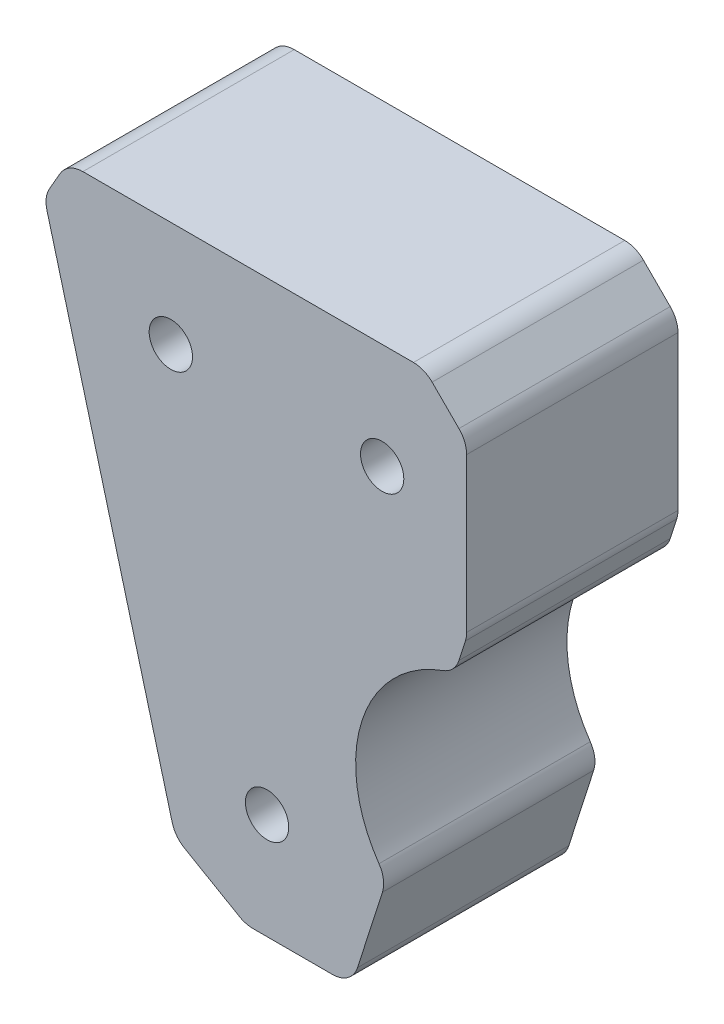
SolidWorks part; units mm, degrees
ref_plane "前视基准面" through (0, 0, 0) normal (0, 0, 1) x (1, 0, 0)
ref_plane "上视基准面" through (0, 0, 0) normal (0, 1, 0) x (1, 0, 0)
ref_plane "右视基准面" through (0, 0, 0) normal (1, 0, 0) x (0, 0, -1)
sketch "草图1" plane through (0, 0, 0) normal (0, 0, 1) x (1, 0, 0)
  line L0 (0, 0) -> (9.1103, -34) construction
  line L1 (-13.0323, 10) -> (1.437, -44)
  line L2 (-13.0323, 10) -> (28, 10)
  line L3 (1.437, -44) -> (17.1103, -44)
  line L4 (28, -10) -> (28, 10)
  line L5 (28, -10) -> (17.1103, -44)
  circle A0 centre (0, 0) radius 2.05
  circle A1 centre (20, 0) radius 2.05
  circle A2 centre (9.1103, -34) radius 2.05
  dimension "D1" = 20
  dimension "D2" = 4.1
  dimension "D4" = 34
  dimension "D5" = 10
  dimension "D7" = 10
  dimension "D8" = 8
  dimension "D9" = 10
  dimension "D3" = 75
  dimension "D6" = 10
  dimension "D10" = 8
extrude "凸台-拉伸1" add sketch "草图1" along normal mid plane 20
chamfer "倒角1" distance 4 angle 45 3 edges at (-13.0323, 10, 0) (1.437, -44, 0) (28, 10, 0)
sketch "草图2" plane through (0, 0, 10) normal (0, 0, 1) x (1, 0, 0)
  line L0 (9.1103, -34) -> (29.9917, -25.6206) construction
  line L1 (20, 0) -> (29.9917, -25.6206) construction
  circle A0 centre (29.9917, -25.6206) radius 12.5
  point P2 (18.3909, -30.2758)
  point P3 (25.45, -13.9749)
  dimension "D1" = 15
  dimension "D3" = 25
  dimension "D2" = 10
extrude "切除-拉伸1" cut sketch "草图2" against normal through all
fillet "圆角1" radius 2.5 10 edges at (28, -10, 0) (17.1103, -44, 0) (7.0939, -44, 0) (0.4017, -40.1363, 0) (-9.7663, 10, 0) (24, 10, 0) (28, 6, 0) (-11.997, 6.1363, 0) (26.874, -13.5157, 0) (20.4215, -33.6617, 0)
